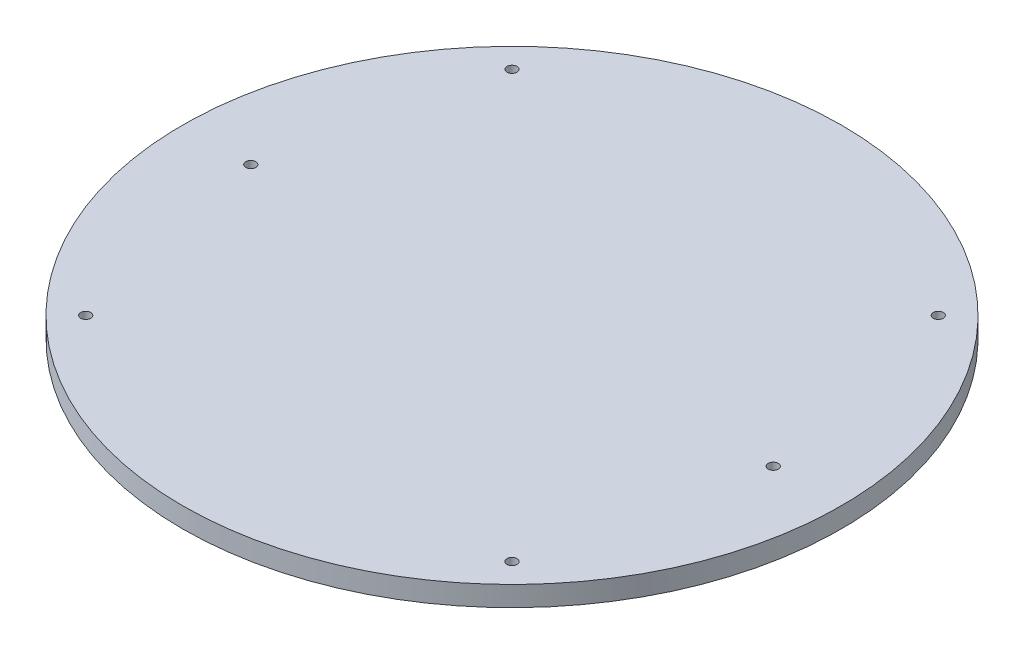
SolidWorks part; units mm, degrees
ref_plane "Front Plane" through (0, 0, 0) normal (0, 0, 1) x (1, 0, 0)
ref_plane "Top Plane" through (0, 0, 0) normal (0, 1, 0) x (1, 0, 0)
ref_plane "Right Plane" through (0, 0, 0) normal (1, 0, 0) x (0, 0, -1)
sketch "Sketch1" plane through (0, 0, 0) normal (0, 1, 0) x (1, 0, 0)
  line L0 (-82, 0) -> (82, 0) construction
  line L1 (0, 82) -> (0, -82) construction
  circle A0 centre (0, 0) radius 82
  dimension "D1" = 164
extrude "Boss-Extrude1" add sketch "Sketch1" along normal blind 5
sketch "Sketch14" plane through (0, 5, 0) normal (0, 1, 0) x (1, 0, 0)
  circle A0 centre (-53.033, 53.033) radius 1.25
  circle A1 centre (53.033, 53.033) radius 1.25
  circle A2 centre (53.033, -53.033) radius 1.25
  circle A3 centre (-53.033, -53.033) radius 1.25
  point P14 (0, 0)
  dimension "D1" = 75
  dimension "D3" = 2.5
  dimension "D2" = 4
extrude "Cut-Extrude2" cut sketch "Sketch14" against normal blind 133
sketch "Sketch15" plane through (0, 5, 0) normal (0, 1, 0) x (1, 0, 0)
  line L0 (-82, 0) -> (82, 0) construction
  circle A0 centre (-65, 0) radius 1.25
  dimension "D1" = 65
extrude "Cut-Extrude3" cut sketch "Sketch15" against normal blind 10
pattern_circular "CirPattern1" count 2 every 180 about axis through (0, 0, 0) along (0, 1, 0) of "Cut-Extrude3"
sketch "Sketch16" plane through (0, 5, 0) normal (0, 1, 0) x (1, 0, 0)
  circle A0 centre (0, 0) radius 4.3756
